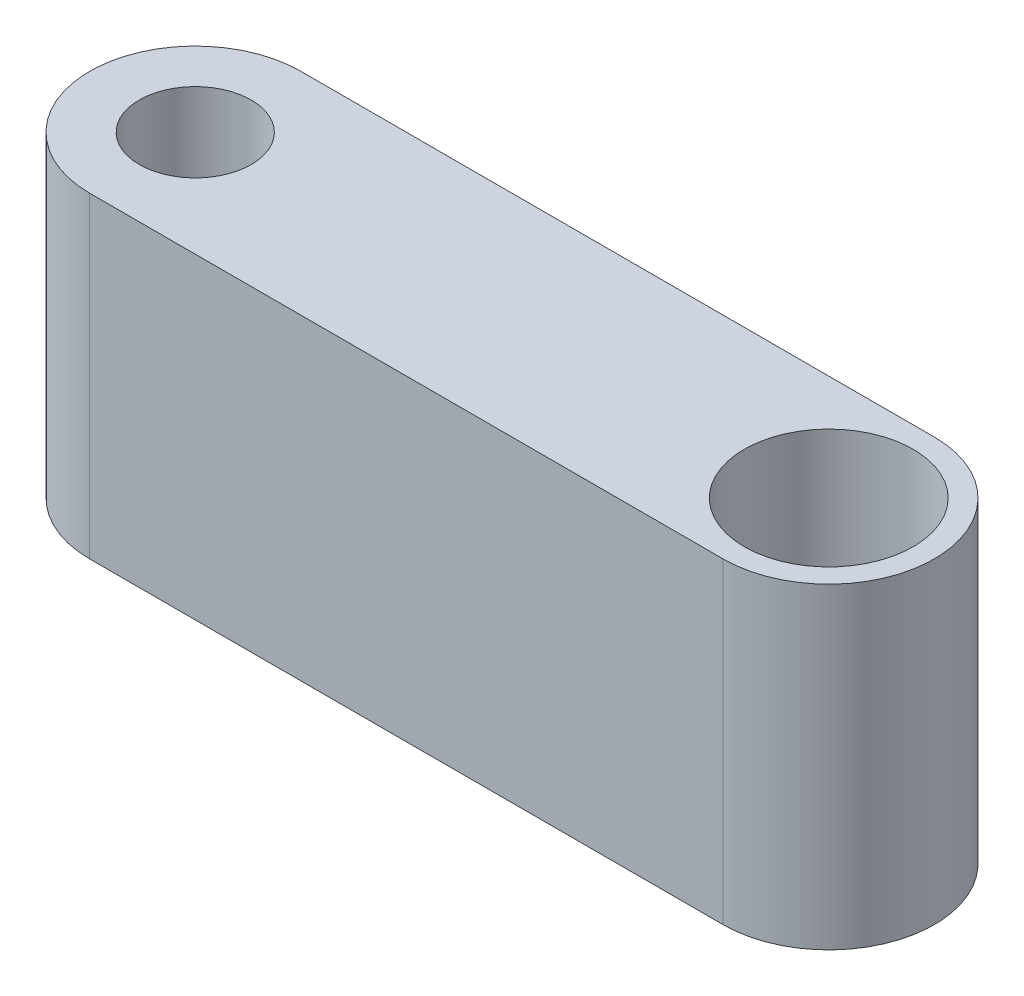
SolidWorks part; units mm, degrees
ref_plane "Front Plane" through (0, 0, 0) normal (0, 0, 1) x (1, 0, 0)
ref_plane "Top Plane" through (0, 0, 0) normal (0, 1, 0) x (1, 0, 0)
ref_plane "Right Plane" through (0, 0, 0) normal (1, 0, 0) x (0, 0, -1)
sketch "Sketch2" plane through (0, 0, 0) normal (0, 1, 0) x (1, 0, 0)
  line L0 (-19.0049, 20.6029) -> (-16.0049, 20.6029) construction
  line L1 (-19.0049, 21.1029) -> (-16.0049, 21.1029)
  line L2 (-19.0049, 20.1029) -> (-16.0049, 20.1029)
  arc A0 (-19.0049, 21.1029) -> (-19.0049, 20.1029) centre (-19.0049, 20.6029) ccw
  arc A1 (-16.0049, 20.1029) -> (-16.0049, 21.1029) centre (-16.0049, 20.6029) ccw
  circle A2 centre (-19.0049, 20.6029) radius 0.265
  circle A3 centre (-16.0049, 20.6029) radius 0.4
  point P2 (-17.5049, 20.6029)
extrude "Boss-Extrude1" add sketch "Sketch2" along normal blind 1.5
